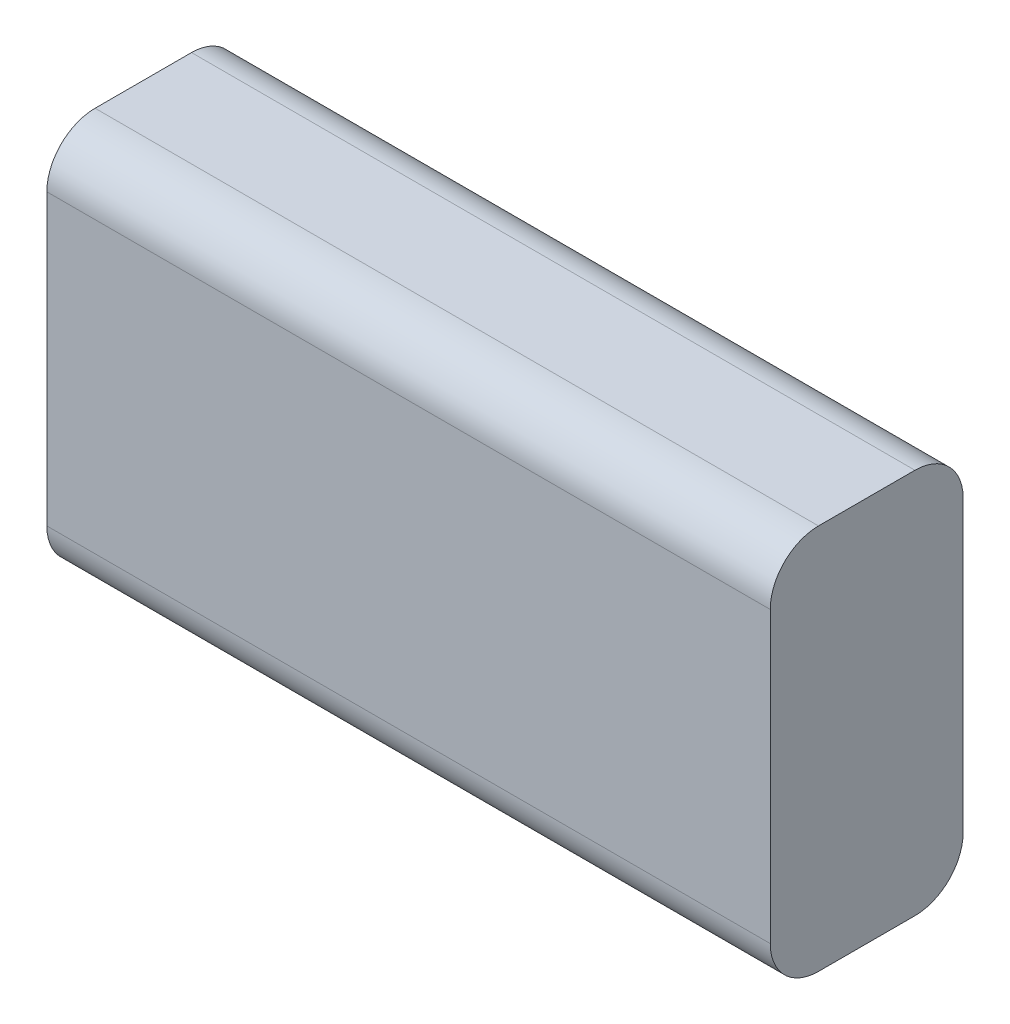
SolidWorks part; units mm, degrees
ref_plane "Alzado" through (0, 0, 0) normal (0, 0, 1) x (1, 0, 0)
ref_plane "Planta" through (0, 0, 0) normal (0, 1, 0) x (1, 0, 0)
ref_plane "Vista lateral" through (0, 0, 0) normal (1, 0, 0) x (0, 0, -1)
sketch "Croquis1" plane through (0, 0, 0) normal (0, 0, 1) x (1, 0, 0)
  line L1 (-37.5, -20) -> (37.5, -20)
  line L2 (-37.5, -20) -> (-37.5, 20)
  line L3 (-37.5, 20) -> (37.5, 20)
  line L4 (37.5, -20) -> (37.5, 20)
  line L5 (-37.5, -20) -> (37.5, 20) construction
  line L6 (-37.5, 20) -> (37.5, -20) construction
  point P0 (0, 0)
  dimension "D1" = 75
  dimension "D2" = 40
extrude "Saliente-Extruir1" add sketch "Croquis1" along normal blind 20
fillet "Redondeo1" radius 5 4 edges at (0, -20, 0) (0, 20, 0) (0, 20, 20) (0, -20, 20)
